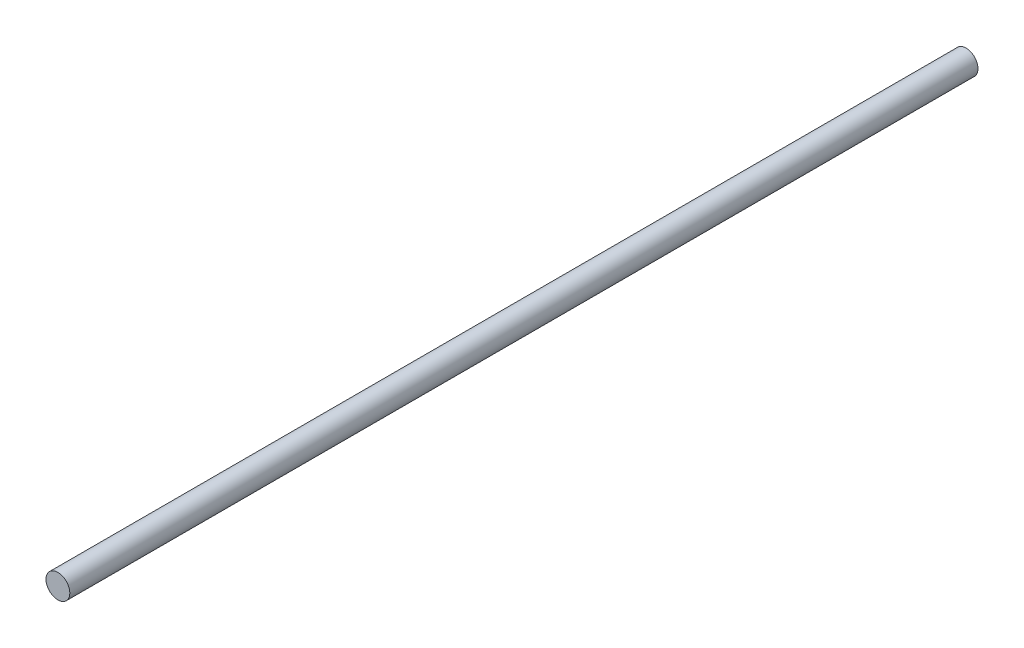
SolidWorks part; units mm, degrees
ref_plane "Front Plane" through (0, 0, 0) normal (0, 0, 1) x (1, 0, 0)
ref_plane "Top Plane" through (0, 0, 0) normal (0, 1, 0) x (1, 0, 0)
ref_plane "Right Plane" through (0, 0, 0) normal (1, 0, 0) x (0, 0, -1)
sketch "Sketch1" plane through (0, 0, 0) normal (0, 0, 1) x (1, 0, 0)
  line L1 (-4, 0) -> (4, 0) construction
  dimension "OD" = 8
sketch "Sketch2" plane through (0, 0, 0) normal (1, 0, 0) x (0, 0, -1)
  line L0 (152.4, 0) -> (-152.4, 0)
  point P4 (0, 0)
  dimension "Length" = 304.8
sketch "Sketch3" plane through (0, 0, 0) normal (0, 0, 1) x (1, 0, 0)
  circle A0 centre (0, 0) radius 4
extrude "Boss-Extrude1" add sketch "Sketch3" along normal up to vertex (152.4 mm away) and the other way up to vertex (152.4 mm away) up to point (0, 0, 152.4) other way up to point (0, 0, -152.4)
